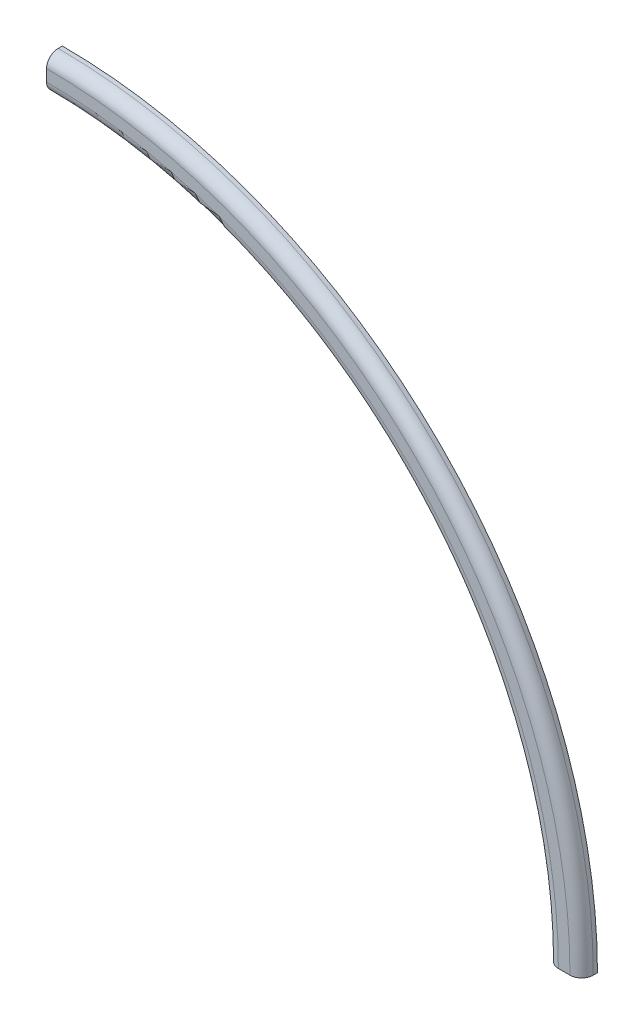
SolidWorks part; units mm, degrees
ref_plane "Front Plane" through (0, 0, 0) normal (0, 0, 1) x (1, 0, 0)
ref_plane "Top Plane" through (0, 0, 0) normal (0, 1, 0) x (1, 0, 0)
ref_plane "Right Plane" through (0, 0, 0) normal (1, 0, 0) x (0, 0, -1)
sketch "Sketch1" plane through (0, 0, 0) normal (0, 0, 1) x (1, 0, 0)
  line L0 (0, 584.2) -> (0, 546.1)
  line L1 (584.2, 0) -> (546.1, 0)
  arc A0 (584.2, 0) -> (0, 584.2) centre (0, 0) ccw
  arc A1 (0, 546.1) -> (546.1, 0) centre (0, 0) cw
  dimension "D1" = 584.2
  dimension "D2" = 546.1
extrude "Boss-Extrude1" add sketch "Sketch1" along normal blind 17.272
sketch "Sketch2" plane through (0, 0, 17.272) normal (0, 0, 1) x (1, 0, 0)
  line L0 (0, 584.2) -> (0, 546.1) construction
  line L1 (546.1, 0) -> (584.2, 0) construction
  line L2 (575.31, 0) -> (554.99, 0)
  line L3 (0, 575.31) -> (0, 554.99)
  arc A0 (0, 575.31) -> (575.31, 0) centre (0, 0) cw
  arc A1 (554.99, 0) -> (0, 554.99) centre (0, 0) ccw
  dimension "D1" = 575.31
  dimension "D2" = 554.99
extrude "Cut-Extrude1" [suppressed] cut sketch "Sketch2" against normal offset from surface (5.08 mm away) 5.08
fillet "Fillet1" [suppressed] radius 6.35
fillet "Fillet2" radius 12.7 2 edges at (413.0918, 413.0918, 17.272) (386.151, 386.151, 17.272)
